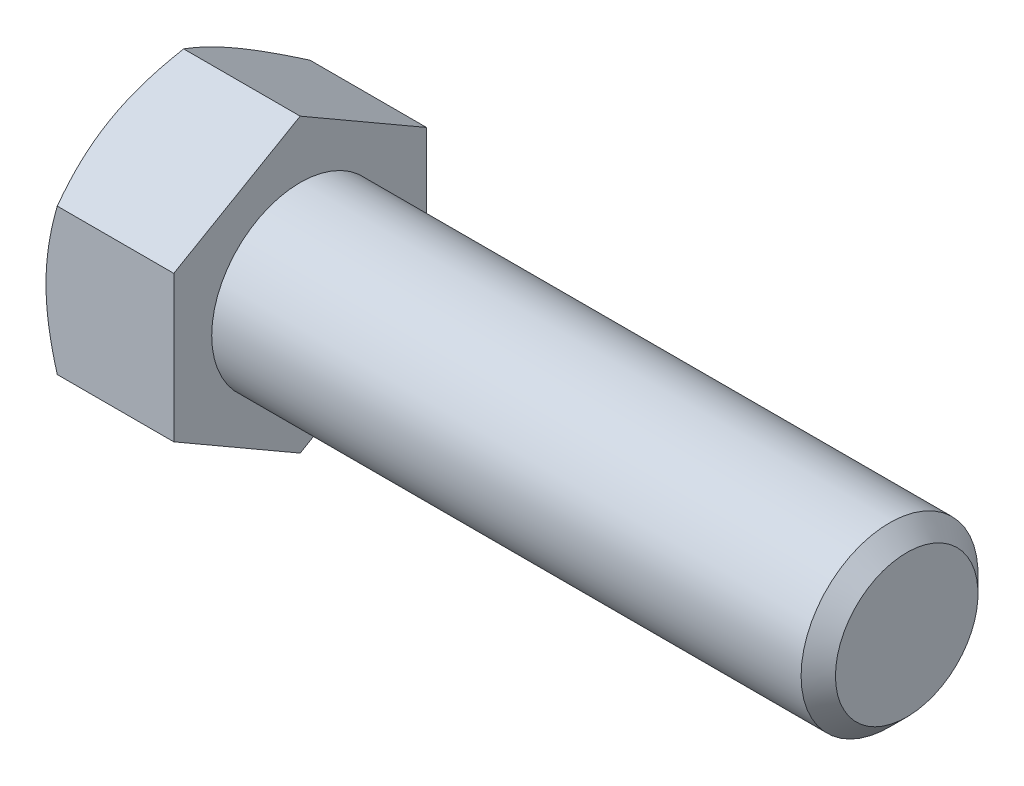
SolidWorks part; units mm, degrees
extrude "BaseHead" add sketch "Sketch1" along normal blind 8.0264
sketch "Sketch1" plane through (0, 0, 0) normal (1, 0, 0) x (0, 0, -1)
  line L0 (7.9375, 4.5827) -> (7.9375, -4.5827)
  line L1 (-7.9375, 4.5827) -> (-7.9375, -4.5827)
  line L2 (7.9375, -4.5827) -> (0, -9.1654)
  line L3 (0, -9.1654) -> (-7.9375, -4.5827)
  line L4 (7.9375, 4.5827) -> (0, 9.1654)
  line L5 (0, 9.1654) -> (-7.9375, 4.5827)
  dimension "Width_flats" = 15.875
  dimension "D2" = 120
  dimension "D3" = 7.9375
  dimension "D4" = 7.9375
  dimension "D5" = 7.9375
ref_plane "Plane1" through (0, 0, 0) normal (0, 0, 1) x (1, 0, 0)
ref_plane "Plane2" through (0, 0, 0) normal (0, 1, 0) x (1, 0, 0)
ref_plane "Plane3" through (0, 0, 0) normal (1, 0, 0) x (0, 0, -1)
other "Configuration Table"
sketch "BodySke" plane through (0, 0, 0) normal (0, 0, 1) x (1, 0, 0)
  line L0 (0, 4.5827) -> (0, -4.5827) construction
  line L1 (0, 0) -> (46.1264, 0)
  line L2 (0, 0) -> (0, 5.5563)
  line L3 (0, 5.5563) -> (45.0469, 5.5563)
  line L4 (46.1264, 0) -> (46.1264, 4.4768)
  line L5 (8.0264, 9.1654) -> (8.0264, 4.5827) construction
  line L6 (46.1264, 4.4768) -> (45.0469, 5.5563)
  line L7 (0, 0) -> (96.52, 0) construction
  line L8 (46.1264, -4.4768) -> (45.0469, -5.5563) construction
  line L9 (0, -5.5563) -> (45.0469, -5.5563) construction
  line L10 (9.84, 15.24) -> (9.84, -2.54) construction
  line L11 (17.5514, 15.24) -> (17.5514, -2.54) construction
  line L12 (8.0264, 4.5827) -> (8.0264, -4.5827) construction
  dimension "Diameter" = 11.1125
revolve "BaseBody" add sketch "BodySke" angle 360 about L7
cosmetic thread "ThreadCosmetic" parameters "Thread_length"=28.575, "Thread_minor"=8.9535
sketch "Sketch3" plane through (0, 0, 0) normal (0, 0, 1) x (1, 0, 0)
  line L0 (0, 7.9375) -> (4.3751, 15.5154)
  line L1 (0, 9.1654) -> (0, 4.5827) construction
  line L2 (4.3751, 15.5154) -> (4.3751, 21.8654)
  line L3 (4.3751, 21.8654) -> (-12.7, 21.8654)
  line L4 (-12.7, 21.8654) -> (-12.7, 7.9375)
  line L5 (-12.7, 7.9375) -> (0, 7.9375)
  line L6 (0, 0) -> (99.06, 0) construction
  line L7 (8.0264, 9.1654) -> (0, 9.1654) construction
  dimension "D1" = 7.9375
  dimension "D2" = 6.35
  dimension "D3" = 12.7
  dimension "D4" = 6.35
  dimension "Head_ch_ang" = 30
revolve "HeadChamfer" cut sketch "Sketch3" angle 360 about L6
fillet "HeadFillet" [suppressed] radius 0.762
sketch "ThdSchSke" plane through (0, 0, 0) normal (0, 0, 1) x (1, 0, 0)
  line L0 (17.5514, -4.4768) -> (16.7955, -5.5562)
  line L1 (17.5514, -4.4768) -> (18.3073, -5.5562)
  line L2 (18.3073, -5.5562) -> (18.3073, -6.9453)
  line L3 (-3.175, 0) -> (5.1513, 0) construction
  line L5 (18.3073, -6.9453) -> (16.7955, -6.9453)
  line L6 (16.7955, -6.9453) -> (16.7955, -5.5562)
  dimension "Thread_minor" = 8.9535
  dimension "Diameter" = 11.1125
  dimension "Start" = 17.5514
revolve "ThreadSchematic" [suppressed] cut sketch "ThdSchSke" angle 360 about L3
pattern_linear "ThdSchPat" [suppressed]
equation "\"D3@Sketch1\" = \"Width_flats@Sketch1\" / 2"
equation "\"D4@Sketch1\" = \"D3@Sketch1\""
equation "\"D5@Sketch1\" = \"D4@Sketch1\""
equation "\"Thread_minor@ThreadCosmetic\" = \"Minor_dia@BodySke\""
equation "\"D1@Sketch3\" = \"Width_flats@Sketch1\" / 2"
equation "\"Thread_length@ThreadCosmetic\" = ((sgn( (\"Length@BodySke\" - \"Advance@BodySke\" ) - \"Thread_nom@BodySke\" )-1)*( (\"Length@BodySke\" - \"Advance@BodySke\" ) - \"Thread_nom@BodySke\" ))/-2+ \"Thread_nom@BodySke\""
equation "\"Thread_minor@ThdSchSke\" = \"Minor_dia@BodySke\""
equation "\"Diameter@ThdSchSke\" = \"Diameter@BodySke\""
equation "\"Overcut@ThdSchSke\" = \"Diameter@BodySke\" * 1.25"
equation "\"Start@ThdSchSke\" = \"Head_ht@BaseHead\" + \"Length@BodySke\" - \"Thread_length@ThreadCosmetic\"  '---Non-countersunk---"
equation "\"Num_threads@ThdSchPat\" = int( \"Thread_length@ThreadCosmetic\" / \"Advance@BodySke\" + 0.999 )  + 1"
equation "\"Advance@ThdSchPat\" = \"Thread_length@ThreadCosmetic\" /  (\"Num_threads@ThdSchPat\" - 1) 'relax it"
equation "\"Num_threads@ThdSchPat\" = \"Num_threads@ThdSchPat\" - sgn( \"Num_threads@ThdSchPat\" - 1) '---chamfered tips only---"
